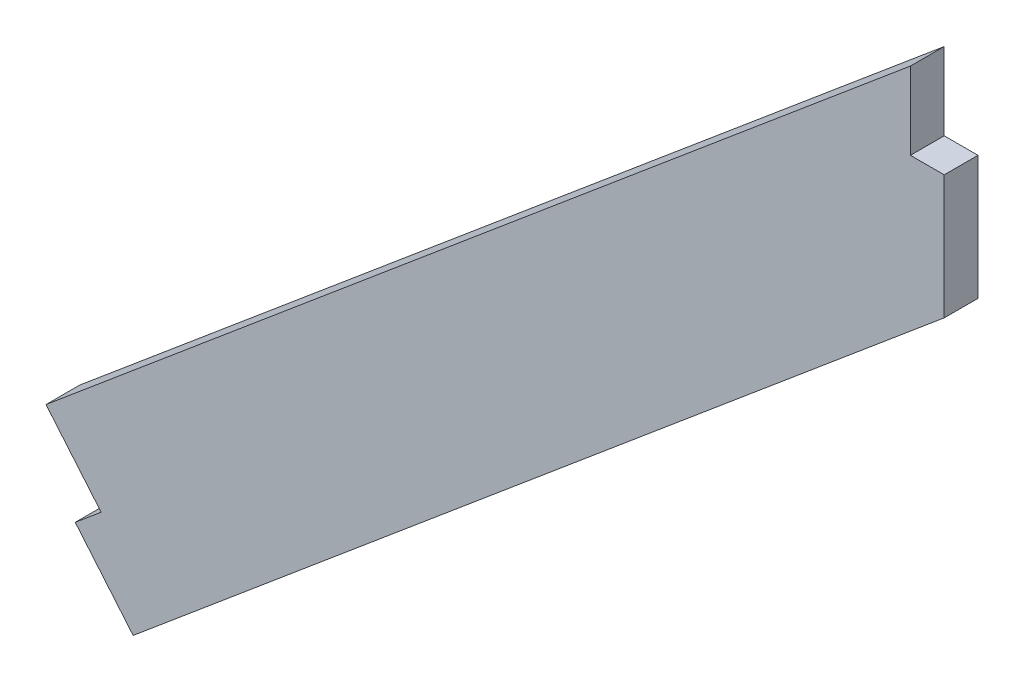
SolidWorks part; units mm, degrees
ref_plane "Front" through (0, 0, 0) normal (0, 0, 1) x (1, 0, 0)
ref_plane "Top" through (0, 0, 0) normal (0, 1, 0) x (1, 0, 0)
ref_plane "Right" through (0, 0, 0) normal (1, 0, 0) x (0, 0, -1)
sketch "Croquis1" plane through (0, 0, 0) normal (0, 0, 1) x (1, 0, 0)
  line L1 (0, -21.34) -> (-72.0082, -81.762)
  line L2 (-72.0082, -81.762) -> (-77.1505, -75.6337)
  line L3 (-79.7455, -67.8738) -> (-3, -3.4767)
  line L4 (-72.0082, -81.762) -> (13.0651, -81.762) construction
  line L5 (0, -21.34) -> (0, -10.34)
  line L6 (-77.1505, -75.6337) -> (-74.8523, -73.7053)
  line L9 (0, -10.34) -> (-3, -10.34)
  line L10 (-3, -3.4767) -> (-3, -10.34)
  line L11 (0, 0) -> (-3, -10.34) construction
  line L13 (-74.8523, -73.7053) -> (-79.7455, -67.8738)
  point P5 (2.4712, 8.5174)
  point P8 (0, 0)
  point P12 (-1.3477, -2.4767)
  dimension "D1" = 10.34
  dimension "D2" = 40
  dimension "D3" = 94
  dimension "D4" = 3
  dimension "D5" = 11
  dimension "D6" = 15.6125
  dimension "D7" = 3
  dimension "D8" = 8
  dimension "D9" = 3
extrude "Saliente-Extruir1" add sketch "Croquis1" along normal blind 3
